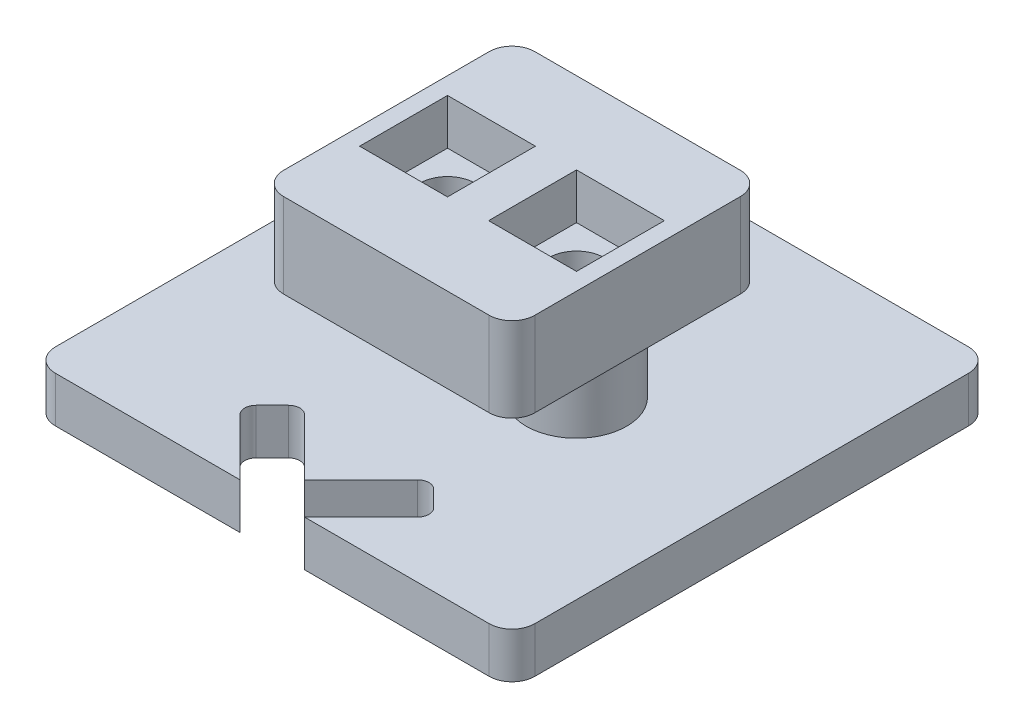
SolidWorks part; units mm, degrees
ref_plane "Front Plane" through (0, 0, 0) normal (0, 0, 1) x (1, 0, 0)
ref_plane "Top Plane" through (0, 0, 0) normal (0, 1, 0) x (1, 0, 0)
ref_plane "Right Plane" through (0, 0, 0) normal (1, 0, 0) x (0, 0, -1)
sketch "Sketch1" plane through (0, 0, 0) normal (0, 1, 0) x (1, 0, 0)
  line L1 (-5.5, -5.5) -> (5.5, -5.5)
  line L2 (-5.5, -5.5) -> (-5.5, 5.5)
  line L3 (-5.5, 5.5) -> (5.5, 5.5)
  line L4 (5.5, -5.5) -> (5.5, 5.5)
  line L5 (-5.5, -5.5) -> (5.5, 5.5) construction
  line L6 (-5.5, 5.5) -> (5.5, -5.5) construction
  point P0 (0, 0)
  dimension "D1" = 11
  dimension "D2" = 11
extrude "Boss-Extrude1" add sketch "Sketch1" along normal blind 3.7
fillet "Fillet1" radius 1 4 edges at (-5.5, 1.85, -5.5) (-5.5, 1.85, 5.5) (5.5, 1.85, -5.5) (5.5, 1.85, 5.5)
sketch "Sketch2" plane through (0, 3.7, 0) normal (0, 1, 0) x (1, 0, 0)
  line L0 (-2.825, 0) -> (2.825, 0) construction
  line L2 (-4.75, -1.925) -> (-0.9, -1.925)
  line L3 (-4.75, -1.925) -> (-4.75, 1.925)
  line L4 (-4.75, 1.925) -> (-0.9, 1.925)
  line L5 (-0.9, -1.925) -> (-0.9, 1.925)
  line L6 (-4.75, -1.925) -> (-0.9, 1.925) construction
  line L7 (-4.75, 1.925) -> (-0.9, -1.925) construction
  line L8 (0.9, -1.925) -> (4.75, -1.925)
  line L9 (0.9, -1.925) -> (0.9, 1.925)
  line L10 (0.9, 1.925) -> (4.75, 1.925)
  line L11 (4.75, -1.925) -> (4.75, 1.925)
  line L12 (0.9, -1.925) -> (4.75, 1.925) construction
  line L13 (0.9, 1.925) -> (4.75, -1.925) construction
  point P4 (0, 0)
  dimension "D1" = 3.85
  dimension "D2" = 3.85
  dimension "D3" = 3.85
  dimension "D4" = 3.85
  dimension "D5" = 5.65
extrude "Cut-Extrude1" cut sketch "Sketch2" against normal blind 2
sketch "Sketch4" plane through (0, 0, 0) normal (0, -1, 0) x (-1, 0, 0)
  line L0 (2.825, 0) -> (-2.825, 0) construction
  circle A0 centre (2.825, 0) radius 2.2
  circle A1 centre (-2.825, 0) radius 2.2
  point P4 (0, 0)
  point P8 (0, 0)
  dimension "D1" = 5.65
  dimension "D2" = 4.4
  dimension "D3" = 4.4
extrude "Boss-Extrude2" add sketch "Sketch4" along normal blind 5
sketch "Sketch5" plane through (0, -5, 0) normal (0, -1, 0) x (-1, 0, 0)
  line L1 (9.5, 10.5) -> (-9.5, 10.5)
  line L2 (10.5, 9.5) -> (10.5, -9.5)
  line L3 (9.5, -10.5) -> (-9.5, -10.5)
  line L4 (-10.5, 9.5) -> (-10.5, -9.5)
  line L5 (10.5, 10.5) -> (-10.5, -10.5) construction
  line L6 (10.5, -10.5) -> (-10.5, 10.5) construction
  arc A0 (10.5, -9.5) -> (9.5, -10.5) centre (9.5, -9.5) cw
  arc A1 (-10.5, -9.5) -> (-9.5, -10.5) centre (-9.5, -9.5) ccw
  arc A2 (-9.5, 10.5) -> (-10.5, 9.5) centre (-9.5, 9.5) ccw
  arc A3 (9.5, 10.5) -> (10.5, 9.5) centre (9.5, 9.5) cw
  point P0 (0, 0)
  dimension "D3" = 1
  dimension "D1" = 21
  dimension "D2" = 21
extrude "Boss-Extrude3" add sketch "Sketch5" against normal blind 2
sketch "Sketch3" plane through (0, 3.7, 0) normal (0, 1, 0) x (1, 0, 0)
  line L0 (-2.825, 0) -> (2.825, 0) construction
  circle A0 centre (-2.825, 0) radius 1.2
  circle A1 centre (2.825, 0) radius 1.2
  point P4 (0, 0)
  point P5 (0, 0)
  point P8 (0, 0)
  dimension "D2" = 2.4
  dimension "D3" = 2.4
  dimension "D1" = 5.65
extrude "Cut-Extrude2" cut sketch "Sketch3" against normal through all
sketch "Sketch7" plane through (0, -3, 0) normal (0, 1, 0) x (1, 0, 0)
  line L0 (9.5, -10.5) -> (-9.5, -10.5) construction
  line L1 (2.8284, -14.7426) -> (4.2426, -13.3284)
  line L2 (2.8284, -14.7426) -> (-3.8891, -8.0251)
  line L3 (-3.8891, -7.318) -> (-3.182, -6.6109)
  line L4 (4.2426, -13.3284) -> (-2.4749, -6.6109)
  line L5 (2.8284, -14.7426) -> (-2.8284, -6.2574) construction
  line L6 (-4.2426, -7.6716) -> (4.2426, -13.3284) construction
  line L8 (-4.2426, -13.3284) -> (-2.8284, -14.7426)
  line L9 (-4.2426, -13.3284) -> (2.4749, -6.6109)
  line L10 (3.182, -6.6109) -> (3.8891, -7.318)
  line L11 (-2.8284, -14.7426) -> (3.8891, -8.0251)
  line L12 (-4.2426, -13.3284) -> (4.2426, -7.6716) construction
  line L13 (2.8284, -6.2574) -> (-2.8284, -14.7426) construction
  arc A0 (-2.4749, -6.6109) -> (-3.182, -6.6109) centre (-2.8284, -6.9645) ccw
  arc A1 (3.8891, -7.318) -> (3.8891, -8.0251) centre (3.5355, -7.6716) cw
  arc A2 (3.182, -6.6109) -> (2.4749, -6.6109) centre (2.8284, -6.9645) ccw
  arc A3 (-3.8891, -7.318) -> (-3.8891, -8.0251) centre (-3.5355, -7.6716) ccw
  point P0 (0, -10.5)
  point P7 (0, -10.5)
  point P12 (-1.4142, -10.5)
  point P13 (1.4142, -10.5)
  line M12 (-9.5, -10.5) -> (9.5, -10.5)
  dimension "D7" = 0.5
  dimension "D8" = 0.5
  dimension "D1" = 2
  dimension "D2" = 45
  dimension "D3" = 2
  dimension "D4" = 45
  dimension "D5" = 4
  dimension "D6" = 4
extrude "Cut-Extrude3" cut sketch "Sketch7" against normal through all contours L10 A2 L9 L4 L11 A1 | L3 A3 L2 L9 L4 A0 | L9 L4 M12
equation "\"D2@Sketch2\"=\"D1@Sketch2\""
equation "\"D3@Sketch2\"=\"D1@Sketch2\""
equation "\"D4@Sketch2\"=\"D1@Sketch2\""
equation "\"D2@Sketch1\"=\"D1@Sketch1\""
equation "\"D3@Sketch3\"=\"D2@Sketch3\""
equation "\"D3@Sketch4\"=\"D2@Sketch4\""
equation "\"D2@Sketch5\"=\"D1@Sketch5\""
equation "\"D3@Sketch7\"=\"D1@Sketch7\""
equation "\"D6@Sketch7\"=\"D5@Sketch7\""
